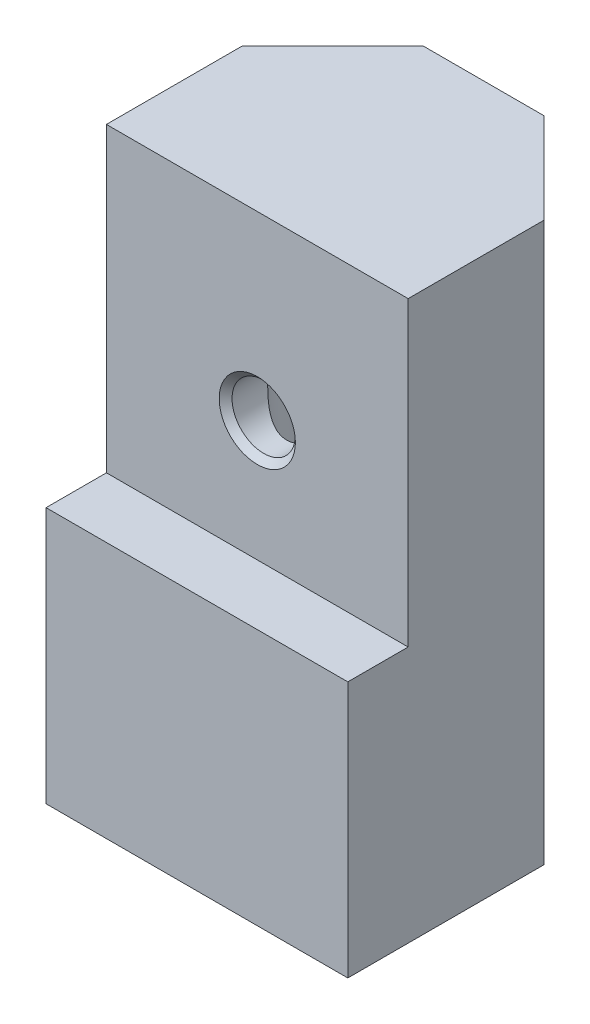
SolidWorks part; units mm, degrees
ref_plane "Front" through (0, 0, 0) normal (0, 0, 1) x (1, 0, 0)
ref_plane "Top" through (0, 0, 0) normal (0, 1, 0) x (1, 0, 0)
ref_plane "Right" through (0, 0, 0) normal (1, 0, 0) x (0, 0, -1)
sketch "Sketch1" plane through (0, 0, 0) normal (0, 0, 1) x (1, 0, 0)
  line L0 (-10, 8.5) -> (0, 0) construction
  line L1 (-10, 8.5) -> (10, 8.5)
  line L2 (-10, 8.5) -> (-10, -8.5)
  line L3 (-10, -8.5) -> (10, -8.5)
  line L4 (10, 8.5) -> (10, -8.5)
  line L5 (0, 0) -> (10, -8.5) construction
  dimension "D1" = 17
  dimension "D2" = 20
extrude "Boss-Extrude1" add sketch "Sketch1" along normal blind 4
sketch "Sketch2" plane through (0, 0, 0) normal (0, 0, -1) x (-1, 0, 0)
  line L0 (10, 8.5) -> (10, -8.5) construction
  line L1 (-10, -8.5) -> (10, -8.5)
  line L2 (-10, -8.5) -> (-10, 28.5)
  line L3 (-10, 28.5) -> (10, 28.5)
  line L4 (10, -8.5) -> (10, 28.5)
  dimension "D1" = 37
extrude "Boss-Extrude2" add sketch "Sketch2" along normal blind 15
hole_wizard "M5 Tapped Hole1" positions "3DSketch1" profile "Sketch4" tap size "M5" standard "ISO"
sketch3d "3DSketch1"
  line L0 (10, 8.5, 0) -> (-10, 8.5, 0) construction
  point P0 (0, 16.5, 0)
  point P5 (0, 8.5, 0)
  dimension "D1" = 8
cosmetic thread "Hole Thread1" parameters "D1"=7.4, "D2"=5
sketch "Sketch4" plane through (0, 16.5, 0) normal (1, 0, 0) x (0, -1, 0)
  line L0 (0, 0) -> (0, 11.0618)
  line L1 (0, 11.0618) -> (2.1, 9.8)
  line L2 (2.1, 9.8) -> (2.1, 0.425)
  line L3 (2.1, 0.425) -> (2.525, 0)
  line L5 (2.525, 0) -> (0, 0)
  line L6 (-2.1, 0.425) -> (-2.525, 0) construction
  line L10 (0, 11.0618) -> (-2.1, 9.8) construction
  line L11 (0, -6.35) -> (0, 107.95) construction
  dimension "Tap Drill Dia." = 4.2
  dimension "Tap Drill Depth" = 9.8
  dimension "Near C'Sink Dia." = 5.05
  dimension "Near C'Sink Angle" = 90
  dimension "Drill Angle" = 118
sketch "Sketch5" plane through (0, -8.5, 0) normal (0, -1, 0) x (1, 0, 0)
  line L0 (10, -15) -> (-10, -15) construction
  circle A0 centre (0, -5) radius 3.05
  dimension "D2" = 6.1
  dimension "D1" = 10
extrude "Cut-Extrude1" cut sketch "Sketch5" against normal blind 25
chamfer "Chamfer1" distance 6 angle 45 2 edges at (-10, 10, -15) (10, 10, -15)
